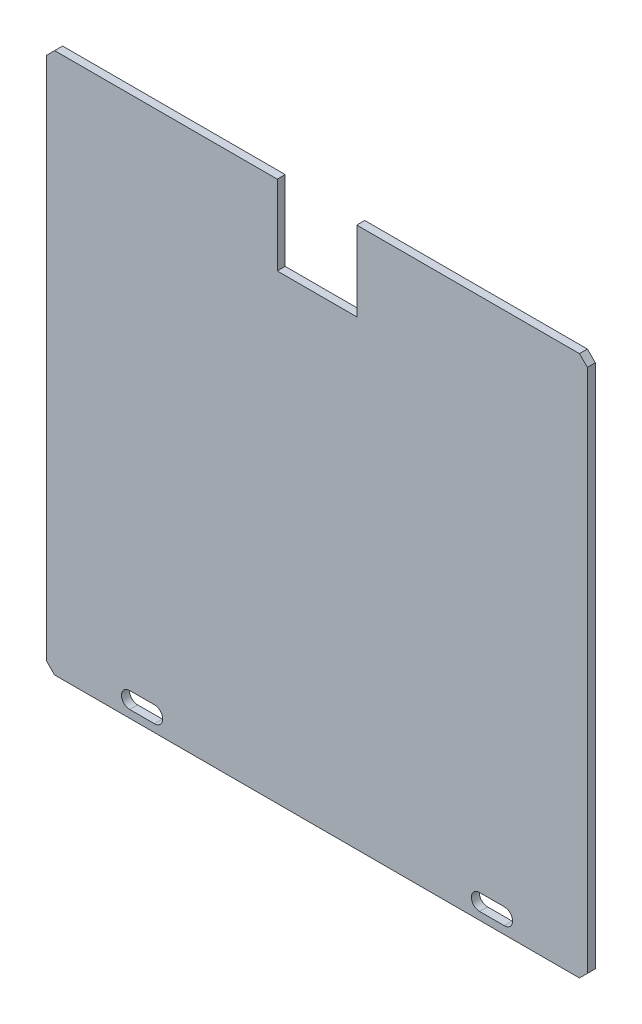
SolidWorks part; units mm, degrees
ref_plane "Front Plane" through (0, 0, 0) normal (0, 0, 1) x (1, 0, 0)
ref_plane "Top Plane" through (0, 0, 0) normal (0, 1, 0) x (1, 0, 0)
ref_plane "Right Plane" through (0, 0, 0) normal (1, 0, 0) x (0, 0, -1)
sketch "Sketch2" plane through (0, 0, 0) normal (0, 0, 1) x (1, 0, 0)
  line L1 (-170, -170) -> (170, -170)
  line L2 (-170, -170) -> (-170, 170)
  line L3 (-170, 170) -> (170, 170)
  line L4 (170, -170) -> (170, 170)
  line L5 (-170, -170) -> (170, 170) construction
  line L6 (-170, 170) -> (170, -170) construction
  point P0 (0, 0)
  dimension "D2" = 340
  dimension "D1" = 340
extrude "Boss-Extrude1" add sketch "Sketch2" along normal blind 5
chamfer "Chamfer1" distance 5 angle 45 4 edges at (170, 170, 2.5) (170, -170, 2.5) (-170, -170, 2.5) (-170, 170, 2.5)
sketch "Sketch4" plane through (0, 0, 5) normal (0, 0, 1) x (1, 0, 0)
  line L0 (-7.8, 160) -> (7.8, 160) construction
  line L1 (0, -2.75) -> (0, 2.75) construction
  line L2 (-7.8, 164.9) -> (7.8, 164.9)
  line L3 (-7.8, 155.1) -> (7.8, 155.1)
  line L4 (165, 170) -> (-165, 170) construction
  line L5 (-117.8, -160) -> (-102.2, -160) construction
  line L6 (-117.8, -154.85) -> (-102.2, -154.85)
  line L7 (-117.8, -165.15) -> (-102.2, -165.15)
  line L8 (-165, -170) -> (165, -170) construction
  line L9 (-170, 165) -> (-170, -165) construction
  arc A0 (-7.8, 164.9) -> (-7.8, 155.1) centre (-7.8, 160) ccw
  arc A1 (7.8, 155.1) -> (7.8, 164.9) centre (7.8, 160) ccw
  arc A2 (-117.8, -154.85) -> (-117.8, -165.15) centre (-117.8, -160) ccw
  arc A3 (-102.2, -165.15) -> (-102.2, -154.85) centre (-102.2, -160) ccw
  point P4 (0, 160)
  point P13 (-110, -160)
  dimension "D1" = 10
  dimension "D2" = 9.8
  dimension "D3" = 15.6
  dimension "D4" = 10
  dimension "D5" = 10.3
  dimension "D6" = 15.6
  dimension "D7" = 60
extrude "Cut-Extrude2" cut sketch "Sketch4" against normal through all
mirror "Mirror1" about plane through (0, 0, 0) normal (1, 0, 0) of "Cut-Extrude2"
sketch "Sketch5" plane through (0, 0, 5) normal (0, 0, 1) x (1, 0, 0)
  line L0 (0, -2.75) -> (0, 2.75) construction
  line L1 (-25, 120) -> (25, 120)
  line L2 (-25, 120) -> (-25, 170)
  line L3 (-25, 170) -> (25, 170)
  line L4 (25, 120) -> (25, 170)
  line L5 (-25, 120) -> (25, 170) construction
  line L6 (-25, 170) -> (25, 120) construction
  line L7 (165, 170) -> (-165, 170) construction
  point P0 (0, 145)
  dimension "D1" = 50
  dimension "D2" = 50
extrude "Cut-Extrude3" cut sketch "Sketch5" against normal through all
equation "\"cork_x\"= \"print_bed_x@print_bed.Assembly\""
equation "\"cork_y\"= \"print_bed_y@print_bed.Assembly\""
equation "\"cork_z\"= 5"
equation "\"D2@Sketch2\"= \"cork_y\""
equation "\"D1@Sketch2\"= \"cork_x\""
equation "\"D1@Boss-Extrude1\"=\"cork_z\""
equation "\"D3@Sketch4\"=25.4 - 9.8"
equation "\"D6@Sketch4\"=\"D3@Sketch4\""
